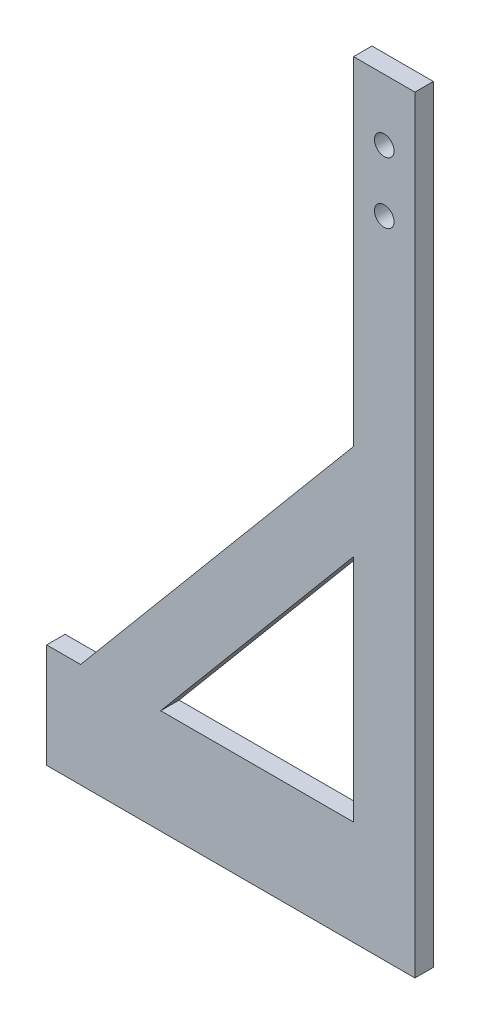
SolidWorks part; units mm, degrees
ref_plane "Ebene vorne" through (0, 0, 0) normal (0, 0, 1) x (1, 0, 0)
ref_plane "Ebene oben" through (0, 0, 0) normal (0, 1, 0) x (1, 0, 0)
ref_plane "Ebene rechts" through (0, 0, 0) normal (1, 0, 0) x (0, 0, -1)
sketch "Skizze1" plane through (0, 0, 0) normal (0, 0, 1) x (1, 0, 0)
  line L0 (-10, 70) -> (-54.4723, 17)
  line L1 (-54.4723, 17) -> (-60, 17)
  line L2 (-60, 17) -> (-60, 0)
  line L3 (-10, 125) -> (0, 125)
  line L4 (0, 0) -> (0, 125)
  line L5 (-60, 0) -> (0, 0)
  line L6 (-10, 54.4428) -> (-41.4182, 17)
  line L7 (-41.4182, 17) -> (-10, 17)
  line L8 (-10, 17) -> (-10, 54.4428)
  line L9 (-10, 70) -> (-10, 125)
  dimension "D1" = 10
  dimension "D2" = 125
  dimension "D3" = 60
  dimension "D4" = 17
  dimension "D5" = 10
  dimension "D6" = 70
  dimension "D7" = 50
extrude "Aufsatz-Linear austragen1" add sketch "Skizze1" along normal blind 3
hole_wizard "Ø3.2 (3.2) Durchmesser Bohrung1" positions "Skizze2" profile "Skizze3" hole size "Ø3.2" standard "DIN"
sketch "Skizze2" plane through (0, 0, 3) normal (0, 0, 1) x (1, 0, 0)
  line L0 (0, 125) -> (-10, 125) construction
  point P0 (-5, 115)
  point P2 (-5, 105)
  point P5 (0, 0)
  point P8 (-5, 125)
  dimension "D1" = 10
  dimension "D2" = 10
sketch "Skizze3" plane through (-5, 115, 3) normal (1, 0, 0) x (0, -1, 0)
  line L0 (0, 0) -> (0, 9.4614)
  line L1 (0, 9.4614) -> (1.6, 8.5)
  line L2 (1.6, 8.5) -> (1.6, 0)
  line L5 (1.6, 0) -> (0, 0)
  line L10 (0, 9.4614) -> (-1.6, 8.5) construction
  line L11 (0, -6.35) -> (0, 107.95) construction
  dimension "Bohrerdurchmesser" = 3.2
  dimension "Bohrungstiefe" = 8.5
  dimension "Spitzenwinkel" = 118
